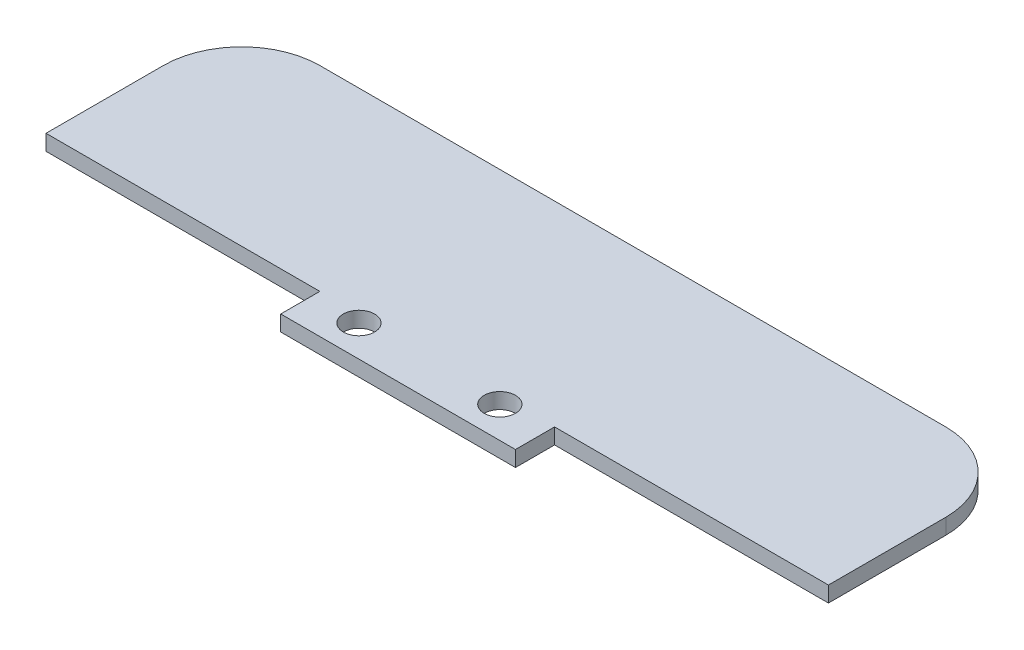
SolidWorks part; units mm, degrees
ref_plane "Front Plane" through (0, 0, 0) normal (0, 0, 1) x (1, 0, 0)
ref_plane "Top Plane" through (0, 0, 0) normal (0, 1, 0) x (1, 0, 0)
ref_plane "Right Plane" through (0, 0, 0) normal (1, 0, 0) x (0, 0, -1)
sketch "Sketch1" plane through (0, 0, 0) normal (0, 1, 0) x (1, 0, 0)
  line L0 (0, 0) -> (0, 10.5) construction
  line L2 (50, 12.5) -> (50, -12.5)
  line L3 (50, -12.5) -> (15, -12.5)
  line L4 (-50, 12.5) -> (-50, -12.5)
  line L5 (50, 12.5) -> (-50, -12.5) construction
  line L6 (50, -12.5) -> (-50, 12.5) construction
  line L7 (-15, -12.5) -> (-15, -17.5)
  line L8 (-15, -17.5) -> (15, -17.5)
  line L9 (15, -17.5) -> (15, -12.5)
  line L10 (-15, -12.5) -> (-50, -12.5)
  line L11 (-50, 12.5) -> (50, 12.5)
  circle A0 centre (-9, -13.5) radius 2
  circle A1 centre (9, -13.5) radius 2
  point P0 (0, 0)
  dimension "D6" = 6
  dimension "D1" = 100
  dimension "D2" = 25
  dimension "D3" = 35
  dimension "D4" = 30
  dimension "D5" = 5
  dimension "D7" = 6
  dimension "D8" = 4
  dimension "D9" = 4
  dimension "D10" = 1
  dimension "D12" = 25
extrude "Boss-Extrude1" add sketch "Sketch1" along normal blind 2
fillet "Fillet1" radius 10 2 edges at (50, 1, -12.5) (-50, 1, -12.5)
